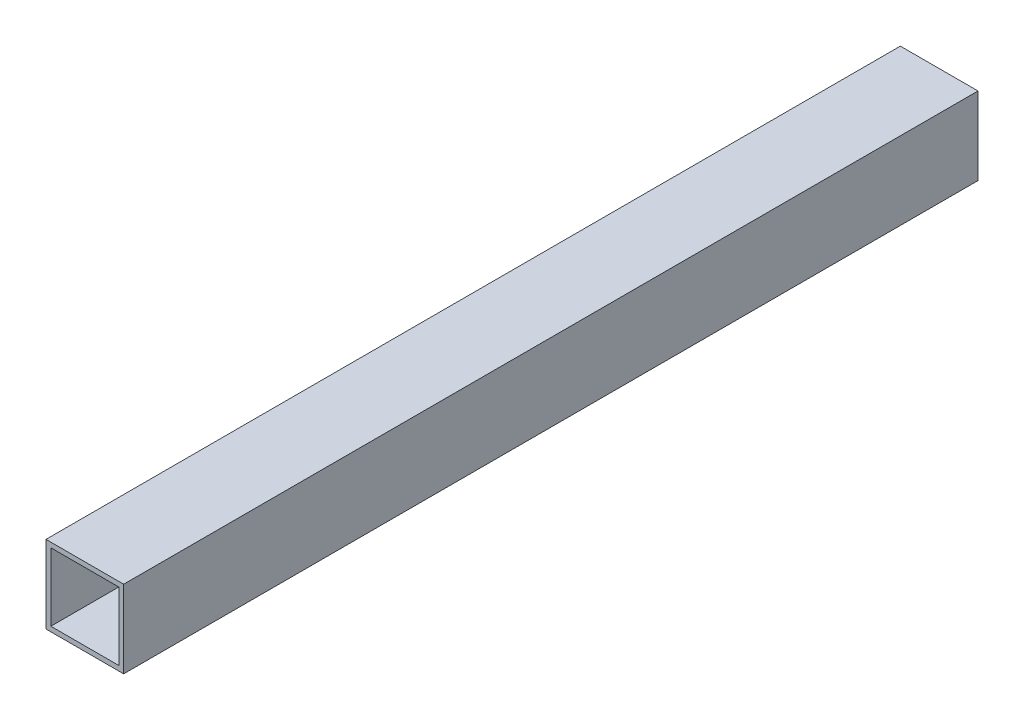
SolidWorks part; units mm, degrees
material "Acrylic (Medium-high impact)"
ref_plane "Front Plane" through (0, 0, 0) normal (0, 0, 1) x (1, 0, 0)
ref_plane "Top Plane" through (0, 0, 0) normal (0, 1, 0) x (1, 0, 0)
ref_plane "Right Plane" through (0, 0, 0) normal (1, 0, 0) x (0, 0, -1)
sketch "Sketch1" plane through (0, 0, 0) normal (0, 0, 1) x (1, 0, 0)
  line L1 (-12.7, 12.7) -> (12.7, 12.7)
  line L2 (-12.7, 12.7) -> (-12.7, -12.7)
  line L3 (-12.7, -12.7) -> (12.7, -12.7)
  line L4 (12.7, 12.7) -> (12.7, -12.7)
  line L5 (-12.7, 12.7) -> (12.7, -12.7) construction
  line L6 (-12.7, -12.7) -> (12.7, 12.7) construction
  line L7 (-11.1125, 11.1125) -> (11.1125, 11.1125)
  line L8 (-11.1125, 11.1125) -> (-11.1125, -11.1125)
  line L9 (-11.1125, -11.1125) -> (11.1125, -11.1125)
  line L10 (11.1125, 11.1125) -> (11.1125, -11.1125)
  line L11 (-11.1125, 11.1125) -> (11.1125, -11.1125) construction
  line L12 (-11.1125, -11.1125) -> (11.1125, 11.1125) construction
  point P0 (0, 0)
  point P6 (0, 0)
  dimension "D1" = 25.4
  dimension "D2" = 1.5875
extrude "Boss-Extrude1" add sketch "Sketch1" along normal mid plane 279.4
